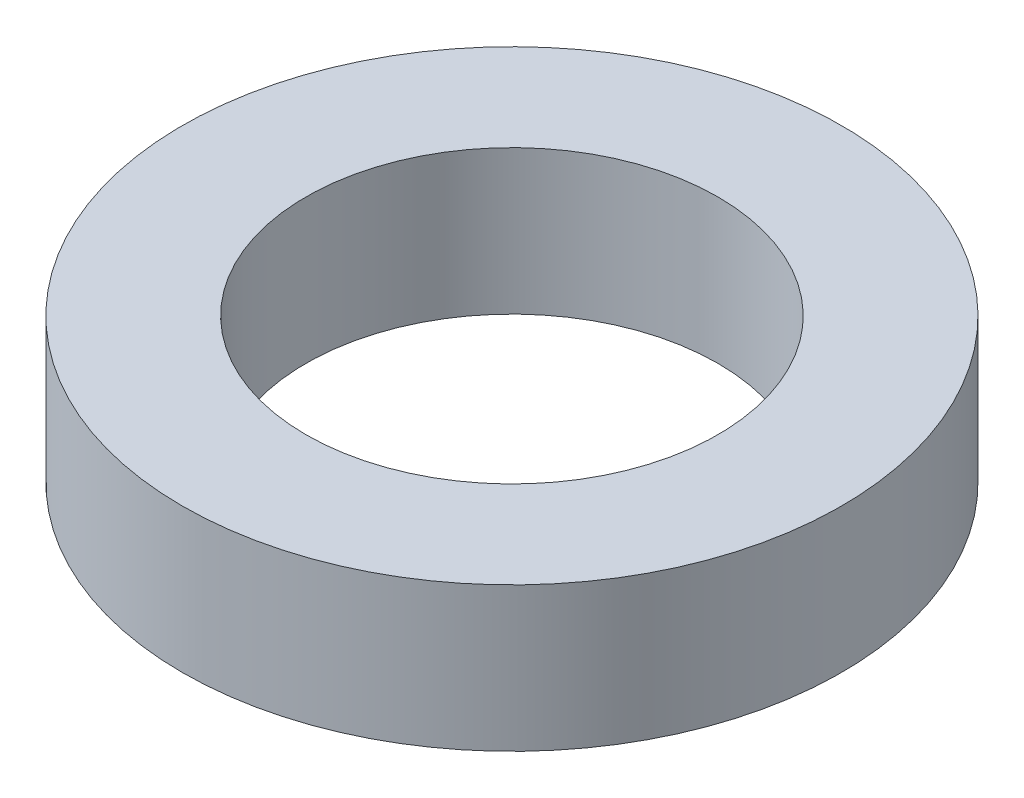
SolidWorks part; units mm, degrees
ref_plane "Front Plane" through (0, 0, 0) normal (0, 0, 1) x (1, 0, 0)
ref_plane "Top Plane" through (0, 0, 0) normal (0, 1, 0) x (1, 0, 0)
ref_plane "Right Plane" through (0, 0, 0) normal (1, 0, 0) x (0, 0, -1)
sketch "Sketch1" plane through (0, 0, 0) normal (0, 1, 0) x (1, 0, 0)
  circle A0 centre (0, 0) radius 16
  circle A1 centre (0, 0) radius 10
  dimension "D1" = 20
  dimension "D2" = 32
extrude "Boss-Extrude1" add sketch "Sketch1" along normal mid plane 7
equation "\"Ns\" = 56"
equation "\"Np_b\" = 48"
equation "\"Np_s\" = 28"
equation "\"Nr_b\" = 152"
equation "\"num_planet\" = 4"
equation "\"module\" = 0.5"
equation "\"fw_p_b\" = 9.918018611286483"
equation "\"fw_r_b\" = 9.918018611286483"
equation "\"fw_s_calc\" = 2.7970255760332914"
equation "\"fw_r_s\" = 14.40536252346366"
equation "\"fw_p_s\" = 15.90536252346366"
equation "\"fw_s_used\" = 33.32338113475014"
equation "\"pressure_angle\" = 20.0"
equation "\"motor_OD\" = 86.8"
equation "\"motor_height\" = 26.5"
equation "\"motor_mount_hole_PCD\" = 32"
equation "\"motor_mount_hole_dia\" = 4"
equation "\"motor_mount_hole_num\" = 4"
equation "\"wire_slot_dist_from_center\" = 38"
equation "\"wire_slot_length\" = 10"
equation "\"wire_slot_radius\" = 2.5"
equation "\"motor_output_hole_PCD\" = 23"
equation "\"motor_output_hole_dia\" = 4"
equation "\"motor_output_hole_num\" = 4"
equation "\"h_a\" = 0.5"
equation "\"h_f\" = 0.625"
equation "\"clr_tip_root\" = 0.125"
equation "\"dp_r_b\" = 76.0"
equation "\"db_r_b\" = 71.41663917972905"
equation "\"alpha_r_b\" = 0.8539582918412236"
equation "\"beta_r_b\" = 2.8921271099982366"
equation "\"bearing_ID\" = 60"
equation "\"bearing_OD\" = 78"
equation "\"bearing_height\" = 10"
equation "\"clearance_planet\" = 1.5"
equation "\"case_dist\" = 6.5"
equation "\"Motor_case_OD_max\" = 111.3"
equation "\"case_mounting_PCD\" = 103.8"
equation "\"bearing mount thickness\" = 8"
equation "\"case_mounting_hole_dia\" = 3"
equation "\"output_mounting_PCD\" = 86"
equation "\"output_mounting_hole_dia\" = 4"
equation "\"clearance_case_mount_holes_shell_thickness\" = 1"
equation "\"motor_case_OD_base\" = 101.8"
equation "\"sec_carrier_thickness\" = 5"
equation "\"sun_coupler_hub_thickness\" = 4"
equation "\"clearance_sun_coupler_sec_carrier\" = 1.5"
equation "\"clearance_motor_and_case\" = 5"
equation "\"Motor_case_thickness\" = 2.5"
equation "\"Motor_case_ID\" = 96.8"
equation "\"case_mounting_hole_shift\" = 1.0"
equation "\"output_mounting_nut_wrench_size\" = 7"
equation "\"output_mounting_nut_thickness\" = 3.2"
equation "\"case_mounting_hole_allen_socket_dia\" = 5.5"
equation "\"output_mounting_nut_depth\" = 3"
equation "\"case_mounting_bolt_depth\" = 4.5"
equation "\"ring_radial_thickness\" = 5"
equation "\"ring_OD_b\" = 86.0"
equation "\"ring_to_chamfer_clearance\" = 1.5"
equation "\"Motor_case_OD_base_to_chamfer\" = 5"
equation "\"pattern_offset_from_motor_case_OD_base\" = 3"
equation "\"pattern_bulge_dia\" = 3"
equation "\"pattern_num_bulge\" = 18"
equation "\"pattern_depth\" = 2"
equation "\"case_mounting_wrench_size\" = 5.5"
equation "\"case_mounting_nut_clearance\" = 2"
equation "\"base_plate_thickness\" = 4"
equation "\"case_mounting_nut_thickness\" = 2.4"
equation "\"case_mounting_surface_height\" = 4"
equation "\"central_hole_offset_from_motor_mount_PCD\" = 5"
equation "\"driver_upper_holes_dist_from_center\" = 29"
equation "\"driver_lower_holes_dist_from_center\" = 13"
equation "\"driver_side_holes_dist_from_center\" = 22.5"
equation "\"driver_mount_holes_dia\" = 3"
equation "\"driver_mount_inserts_OD\" = 4.8"
equation "\"driver_mount_thickness\" = 1.5"
equation "\"driver_mount_height\" = 6"
equation "\"air_flow_hole_offset\" = 3"
equation "\"pressure angle\" = 20.0"
equation "\"h_b\" = 0.625"
equation "\"planet_pin_bolt_dia\" = 5"
equation "\"planet_pin_socket_head_dia\" = 8.5"
equation "\"carrier_PCD\" = 52.0"
equation "\"planet_shaft_dia\" = 8"
equation "\"planet_shaft_step_offset\" = 1"
equation "\"carrier_trapezoidal_support_sun_offset\" = 5"
equation "\"carrier_trapezoidal_support_hole_PCD_offset_bearing_ID\" = 4"
equation "\"carrier_trapezoidal_support_hole_dia\" = 3"
equation "\"carrier_trapezoidal_support_hole_socket_head_dia\" = 5.5"
equation "\"carrier_bearing_step_width\" = 1.5"
equation "\"standard_clearance_1_5mm\" = 1.5"
equation "\"standard_fillet_1_5mm\" = 1.5"
equation "\"sun_shaft_bearing_ID\" = 8"
equation "\"sun_shaft_bearing_OD\" = 16"
equation "\"sun_shaft_bearing_width\" = 5"
equation "\"standard_bearing_insertion_chamfer\" = 0.5"
equation "\"carrier_trapezoidal_support_hole_wrench_size\" = 5.5"
equation "\"planet_pin_bolt_wrench_size\" = 8"
equation "\"planet_bearing_OD\" = 12"
equation "\"planet_bearing_width\" = 3.5"
equation "\"planet_bore\" = 10"
equation "\"dp_s\" = 28.0"
equation "\"db_s\" = 26.311393382005434"
equation "\"alpha_s\" = 0.8539582918412485"
equation "\"beta_s\" = 1.5063691306032174"
equation "\"dp_p_b\" = 24.0"
equation "\"db_p_b\" = 22.552622898861802"
equation "\"alpha_p_b\" = 0.8539582918412414"
equation "\"beta_p_b\" = 2.042083416317517"
equation "\"sun_hub_dia\" = 30.0"
equation "\"sun_central_bolt_dia\" = 5"
equation "\"sun_central_bolt_socket_head_dia\" = 8.5"
equation "\"motor_output_hole_CSK_OD\" = 8"
equation "\"motor_output_hole_CSK_head_height\" = 2.0"
equation "\"bearing_retainer_thickness\" = 2"
equation "\"dp_p_s\" = 14.0"
equation "\"db_p_s\" = 13.155696691002717"
equation "\"alpha_p_s\" = 0.8539582918412485"
equation "\"beta_p_s\" = 4.720654844888932"
equation "\"Nr_s\" = 132"
equation "\"clr_tip_root_s\" = 0.125"
equation "\"dp_r_s\" = 66.0"
equation "\"db_r_s\" = 62.01971297186996"
equation "\"alpha_r_s\" = 0.8539582918412449"
equation "\"beta_r_s\" = 3.071552947318853"
equation "\"small_ring_case_thickness\" = 4"
equation "\"carrier_thickness\" = 4"
equation "\"small_ring_output_wall_thickness\" = 5"
equation "\"small_ring_output_wall_to_bearing_shaft_attachement_hole_dia\" = 4"
equation "\"small_ring_output_wall_to_bearing_shaft_attachement_hole_depth\" = 6.5"
equation "\"small_ring_output_wall_to_bearing_shaft_attachement_nut_wrench\" = 7"
equation "\"small_ring_output_wall_to_bearing_shaft_attachement_nut_thickness\" = 3.2"
equation "\"small_ring_output_wall_to_bearing_shaft_attachement_hole_pcd\" = 12"
equation "\"small_ring_output_wall_to_bearing_shaft_attachement_hole_num\" = 3"
equation "\"small_ring_output_wall_to_bearing_shaft_attachement_hole_CSK_OD\" = 8"
equation "\"small_ring_output_wall_to_bearing_shaft_attachement_hole_CSK_head_height\" = 2.0"
equation "\"carrier_small_ring_inner_bearing_ID\" = 20"
equation "\"carrier_small_ring_inner_bearing_OD\" = 32"
equation "\"carrier_small_ring_inner_bearing_height\" = 7"
equation "\"carrier_small_ring_inner_bearing_flap\" = 2"
equation "\"D1@Boss-Extrude1\"=\"carrier_small_ring_inner_bearing_height\""
equation "\"D1@Sketch1\"=\"carrier_small_ring_inner_bearing_ID\""
equation "\"D2@Sketch1\"=\"carrier_small_ring_inner_bearing_OD\""
